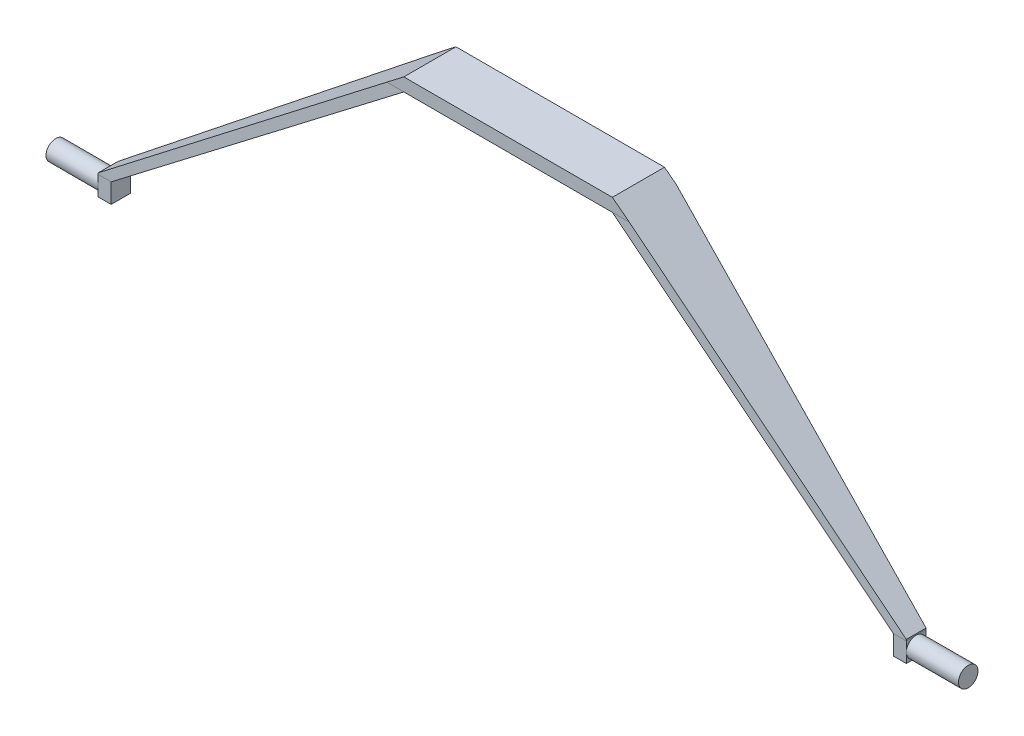
SolidWorks part; units mm, degrees
ref_plane "Front" through (0, 0, 0) normal (0, 0, 1) x (1, 0, 0)
ref_plane "Top" through (0, 0, 0) normal (0, 1, 0) x (1, 0, 0)
ref_plane "Right" through (0, 0, 0) normal (1, 0, 0) x (0, 0, -1)
sketch "Sketch1" plane through (0, 0, 0) normal (0, 0, 1) x (1, 0, 0)
  line L0 (-812.8, -247.65) -> (-812.8, -209.55) construction
  line L1 (-812.8, -228.6) -> (812.8, -228.6) construction
  line L2 (-812.8, -228.6) -> (-812.8, 228.6) construction
  line L3 (-812.8, 228.6) -> (812.8, 228.6) construction
  line L4 (812.8, -228.6) -> (812.8, 228.6) construction
  line L5 (-812.8, -228.6) -> (812.8, 228.6) construction
  line L6 (-812.8, 228.6) -> (812.8, -228.6) construction
  line L7 (-787.4, -228.6) -> (-203.2, -228.6) construction
  line L8 (-787.4, -228.6) -> (-787.4, 228.6) construction
  line L9 (-787.4, 228.6) -> (-203.2, 228.6) construction
  line L10 (-203.2, -228.6) -> (-203.2, 228.6) construction
  line L11 (-787.4717, -247.65) -> (-762.0717, -247.65)
  line L12 (-762.0717, -247.65) -> (-762.0717, -209.55)
  line L13 (-762.0717, -209.55) -> (-203.2, 215.9)
  line L14 (-203.2, 228.6) -> (0, 228.6) construction
  line L15 (-787.4717, -247.65) -> (-787.4, -209.55)
  line L16 (-787.4, -209.55) -> (-787.4, -207.01)
  line L17 (-787.4, -207.01) -> (-203.2, 241.3)
  line L18 (-203.2, 228.6) -> (-203.2, 241.3) construction
  line L19 (-203.2, 228.6) -> (-203.2, 215.9) construction
  line L20 (-203.2, 241.3) -> (203.2, 241.3)
  line L21 (0, 241.3) -> (0, 215.9)
  line L22 (203.2, 215.9) -> (-203.2, 215.9)
  line L23 (0, 228.6) -> (0, -411.3013) construction
  line L24 (787.4, -207.01) -> (203.2, 241.3)
  line L25 (787.4, -209.55) -> (787.4, -207.01)
  line L26 (787.4717, -247.65) -> (787.4, -209.55)
  line L27 (787.4717, -247.65) -> (762.0717, -247.65)
  line L28 (762.0717, -247.65) -> (762.0717, -209.55)
  line L29 (762.0717, -209.55) -> (203.2, 215.9)
  point P0 (0, 0)
  point P13 (-812.8, -228.6)
  dimension "D1" = 1625.6
  dimension "D2" = 457.2
  dimension "D3" = 25.4
  dimension "D4" = 584.2
  dimension "D5" = 38.1
  dimension "D6" = 203.2
  dimension "D7" = 25.4
  dimension "D8" = 2.54
  dimension "D9" = 12.7
  dimension "D10" = 12.7
extrude "Boss-Extrude1" add sketch "Sketch1" against normal blind 101.6 and the other way blind 11.43 contours L22 L21 L20 L17 L16 L15 L11 L12 L13 | L29 L28 L27 L26 L25 L24 L20 L21 L22
sketch "Sketch2" plane through (-787.0031, 1.4803, 0) normal (-1, 0.0019, 0) x (0, 0, 1)
  line L0 (-101.6, -249.1307) -> (11.43, -249.1307) construction
  line L2 (11.43, -246.1684) -> (11.43, -208.0686) construction
  circle A0 centre (-7.62, -230.0807) radius 19.05
  dimension "D1" = 38.1
  dimension "D2" = 19.05
  dimension "D3" = 19.05
extrude "Boss-Extrude2" add sketch "Sketch2" along normal blind 101.6 contours A0
mirror "Mirror1" about plane through (0, 0, 0) normal (1, 0, 0) of "Boss-Extrude2"
sketch "Sketch4" plane through (0, 0, 0) normal (1, 0, 0) x (0, 0, -1)
  line L0 (50.8, -228.6) -> (7.62, -228.6)
  line L1 (101.6, -247.65) -> (101.6, -209.55) construction
  line L2 (7.62, -228.6) -> (-11.43, -228.6)
  dimension "D1" = 43.18
  dimension "D2" = 50.8
  dimension "D3" = 19.05
sketch "Sketch5" plane through (0, 0, 0) normal (1, 0, 0) x (0, 0, -1)
  line L4 (-11.43, -209.55) -> (0, 215.9)
  line L6 (-11.43, -207.01) -> (-11.43, 241.3) construction
  line L7 (-11.43, 215.9) -> (-11.43, -209.55)
  line L9 (-11.43, 215.9) -> (-11.43, 241.3)
  line L12 (0, 241.3) -> (-11.43, 241.3)
  line L14 (0, 241.3) -> (0, 215.9)
  dimension "D1" = 11.43
extrude "Cut-Extrude2" cut sketch "Sketch5" against normal up to next and the other way up to next
sketch "Sketch7" plane through (0, 0, 0) normal (1, 0, 0) x (0, 0, -1)
  line L0 (26.67, -209.55) -> (101.6, 223.9824)
  line L1 (-11.43, -209.55) -> (101.6, -209.55) construction
  line L2 (101.6, -207.01) -> (101.6, 241.3) construction
  line L3 (101.6, 223.9824) -> (101.6, -247.65)
  line L4 (101.6, -247.65) -> (26.67, -247.65)
  line L5 (7.62, -247.65) -> (101.6, -247.65) construction
  line L6 (26.67, -247.65) -> (26.67, -209.55)
extrude "Cut-Extrude3" cut sketch "Sketch7" against normal up to next and the other way up to next
